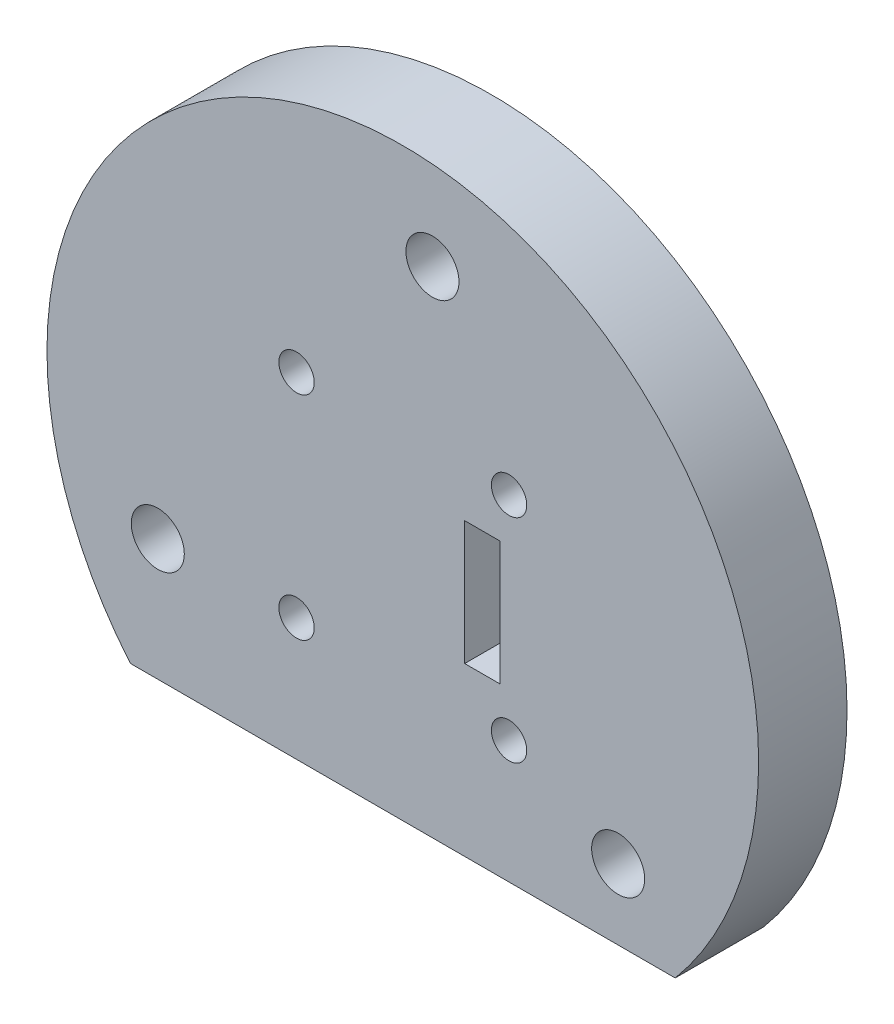
SolidWorks part; units mm, degrees
ref_plane "Front Plane" through (0, 0, 0) normal (0, 0, 1) x (1, 0, 0)
ref_plane "Top Plane" through (0, 0, 0) normal (0, 1, 0) x (1, 0, 0)
ref_plane "Right Plane" through (0, 0, 0) normal (1, 0, 0) x (0, 0, -1)
sketch "Sketch1" plane through (0, 0, 0) normal (0, 0, 1) x (1, 0, 0)
  line L0 (1.347, -41.0396) -> (-10.6738, -41.0396) construction
  line L1 (-10.6738, -41.0396) -> (-4.6634, -41.0396) construction
  line L3 (-1.1634, -43.55) -> (0.8366, -43.55)
  line L4 (10.7452, -60) -> (-20.0721, -60)
  line L6 (-1.1634, -43.55) -> (-1.1634, -50.55)
  line L7 (-1.1634, -50.55) -> (0.8366, -50.55)
  line L8 (0.8366, -43.55) -> (0.8366, -50.55)
  circle A0 centre (7.5187, -56.0192) radius 1.5
  circle A1 centre (-18.5221, -53.1154) radius 1.5
  circle A2 centre (-2.9869, -32.0154) radius 1.5
  circle A3 centre (-4.6634, -47.05) radius 15.1278 construction
  arc A4 (10.7452, -60) -> (-20.0721, -60) centre (-4.6634, -47.05) ccw
  circle A5 centre (1.347, -41.0396) radius 1
  circle A7 centre (1.347, -53.0604) radius 1
  circle A8 centre (-10.6738, -53.0604) radius 1
  circle A9 centre (-10.6738, -41.0396) radius 1
  circle A10 centre (7.5187, -56.0192) radius 4.1778 construction
  circle A13 centre (-4.6634, -47.05) radius 20.1278 construction
  point P0 (-4.6634, -47.05)
  dimension "D1" = 3
  dimension "D4" = 2
  dimension "D3" = 5
  dimension "D5" = 4
extrude "Boss-Extrude1" add sketch "Sketch1" along normal blind 5
